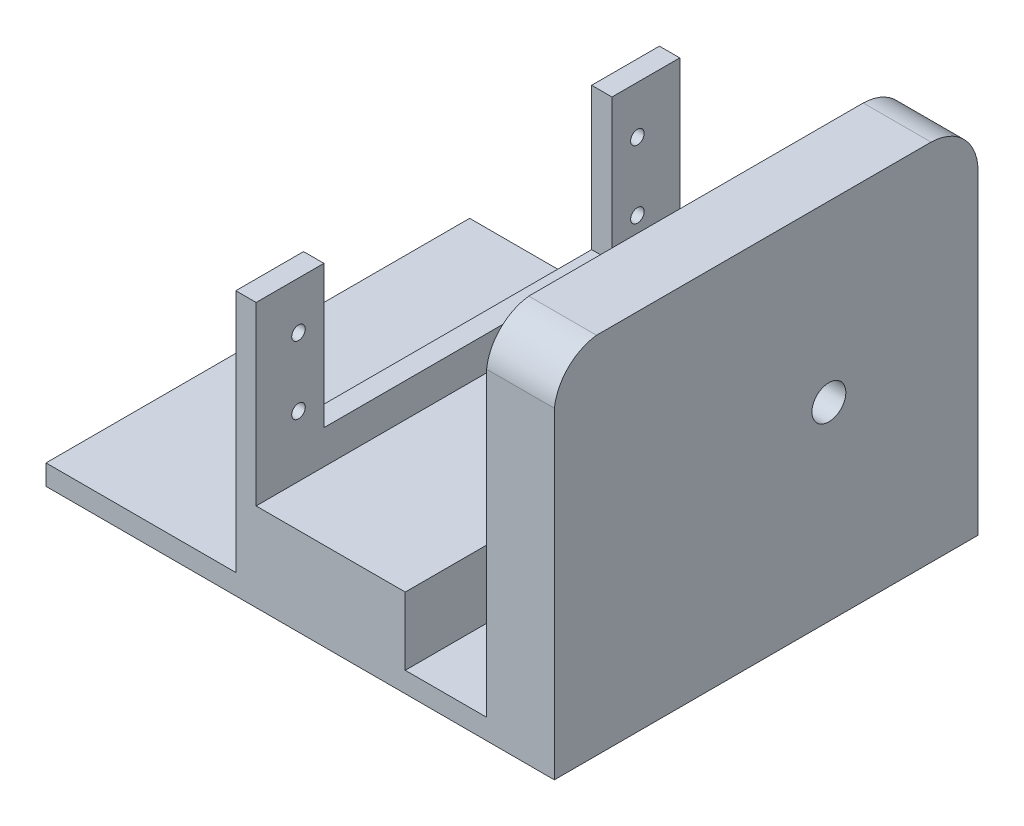
SolidWorks part; units mm, degrees
ref_plane "Front Plane" through (0, 0, 0) normal (0, 0, 1) x (1, 0, 0)
ref_plane "Top Plane" through (0, 0, 0) normal (0, 1, 0) x (1, 0, 0)
ref_plane "Right Plane" through (0, 0, 0) normal (1, 0, 0) x (0, 0, -1)
sketch "Sketch1" plane through (0, 0, 0) normal (0, 1, 0) x (1, 0, 0)
  line L1 (0, 0) -> (99, 0)
  line L2 (0, 0) -> (0, 62.5)
  line L3 (0, 62.5) -> (99, 62.5)
  line L4 (99, 0) -> (99, 62.5)
  dimension "D1" = 99
  dimension "D2" = 62.5
extrude "Boss-Extrude1" add sketch "Sketch1" along normal blind 53.7
sketch "Sketch2" plane through (0, 53.7, 0) normal (0, 1, 0) x (1, 0, 0)
  line L0 (99, 62.5) -> (0, 62.5) construction
  line L1 (10, 62.5) -> (89, 62.5)
  line L2 (10, 62.5) -> (10, 0)
  line L3 (10, 0) -> (89, 0)
  line L4 (89, 62.5) -> (89, 0)
  line L5 (0, 0) -> (99, 0) construction
  line L6 (0, 62.5) -> (0, 0) construction
  line L7 (99, 0) -> (99, 62.5) construction
  dimension "D1" = 10
  dimension "D2" = 10
extrude "Cut-Extrude1" cut sketch "Sketch2" against normal blind 50.7
sketch "Sketch3" plane through (0, 3, 0) normal (0, 1, 0) x (1, 0, 0)
  line L0 (89, 62.5) -> (10, 62.5) construction
  line L1 (77, 62.5) -> (52, 62.5)
  line L2 (77, 62.5) -> (77, 0)
  line L3 (77, 0) -> (52, 0)
  line L4 (52, 62.5) -> (52, 0)
  line L5 (10, 0) -> (89, 0) construction
  line L6 (89, 0) -> (89, 62.5) construction
  dimension "D1" = 12
  dimension "D2" = 25
extrude "Boss-Extrude2" add sketch "Sketch3" along normal blind 10
sketch "Sketch4" plane through (52, 0, 0) normal (-1, 0, 0) x (0, 0, 1)
  line L0 (-62.5, 13) -> (-62.5, 39)
  line L1 (-62.5, 53.7) -> (-62.5, 0) construction
  line L2 (-62.5, 39) -> (-52.5, 39)
  line L3 (-52.5, 39) -> (-52.5, 18)
  line L4 (-52.5, 18) -> (-10, 18)
  line L5 (-10, 18) -> (-10, 39)
  line L6 (-10, 39) -> (0, 39)
  line L7 (0, 53.7) -> (0, 0) construction
  line L8 (0, 39) -> (0, 13)
  line L9 (0, 13) -> (-62.5, 13)
  dimension "D1" = 10
  dimension "D2" = 10
  dimension "D3" = 26
  dimension "D4" = 26
  dimension "D5" = 21
extrude "Boss-Extrude4" add sketch "Sketch4" against normal blind 3
sketch "Sketch5" plane through (0, 0, 0) normal (0, -1, 0) x (1, 0, 0)
  line L1 (99, -62.5) -> (0, -62.5) construction
  line L2 (0, 0) -> (24, 0)
  line L3 (0, 0) -> (0, -62.5)
  line L4 (0, -62.5) -> (24, -62.5)
  line L6 (24, 0) -> (24, -62.5)
  line L7 (99, 0) -> (99, -62.5) construction
  dimension "D1" = 75
extrude "Cut-Extrude3" cut sketch "Sketch5" against normal blind 72
sketch "Sketch6" plane through (52, 0, 0) normal (-1, 0, 0) x (0, 0, 1)
  line L0 (-52.5, 39) -> (-62.5, 39) construction
  line L1 (0, 39) -> (-10, 39) construction
  line L2 (-10, 39) -> (-10, 18) construction
  line L3 (-52.5, 18) -> (-52.5, 39) construction
  circle A0 centre (-56.25, 32) radius 1
  circle A1 centre (-56.25, 22) radius 1
  circle A2 centre (-6.25, 22) radius 1
  circle A3 centre (-6.25, 32) radius 1
  point P8 (-57.5, 39)
  dimension "D1" = 2
  dimension "D2" = 2
  dimension "D3" = 2
  dimension "D4" = 2
  dimension "D5" = 10
  dimension "D6" = 10
  dimension "D7" = 7
  dimension "D8" = 7
  dimension "D9" = 3.75
  dimension "D10" = 3.75
  dimension "D11" = 3.75
  dimension "D12" = 3.75
extrude "Cut-Extrude4" cut sketch "Sketch6" against normal up to next
sketch "Sketch7" plane through (99, 0, 0) normal (1, 0, 0) x (0, 0, -1)
  line L0 (62.5, 53.7) -> (62.5, 0) construction
  line L1 (0, 0) -> (62.5, 0) construction
  circle A0 centre (40.5, 28) radius 2.5
  dimension "D3" = 5
  dimension "D1" = 22
  dimension "D2" = 28
extrude "Cut-Extrude5" cut sketch "Sketch7" against normal blind 72
sketch "Sketch8" plane through (99, 0, 0) normal (1, 0, 0) x (0, 0, -1)
  line L1 (0, 53.7) -> (62.5, 53.7)
  line L2 (0, 53.7) -> (0, 0)
  line L3 (0, 0) -> (62.5, 0)
  line L4 (62.5, 53.7) -> (62.5, 0)
  dimension "D1" = 53.7
  dimension "D2" = 62.5
sketch "Sketch9" plane through (52, 0, 0) normal (-1, 0, 0) x (0, 0, 1)
sketch "Sketch10" plane through (99, 0, 0) normal (1, 0, 0) x (0, 0, -1)
  line L0 (0, 53.7) -> (0, 0) construction
  line L1 (0, 53.7) -> (62.5, 53.7) construction
  line L2 (62.5, 53.7) -> (62.5, 0) construction
  line L3 (0, 45.7646) -> (0, 53.7)
  line L4 (0, 53.7) -> (6.2188, 53.7)
  line L5 (55.5691, 53.7) -> (62.5, 53.7)
  line L6 (62.5, 46.6229) -> (62.5, 53.7)
  arc A0 (0, 45.7646) -> (6.2188, 53.7) centre (7.0771, 46.6229) cw
  arc A1 (62.5, 46.6229) -> (55.5691, 53.7) centre (55.42, 46.6216) ccw
  line M5 (0, 53.7) -> (0, 0)
  dimension "D1" = 7.0771
extrude "Cut-Extrude7" cut sketch "Sketch10" against normal blind 50 contours A0 L4 M5 | A1 L5 L6
